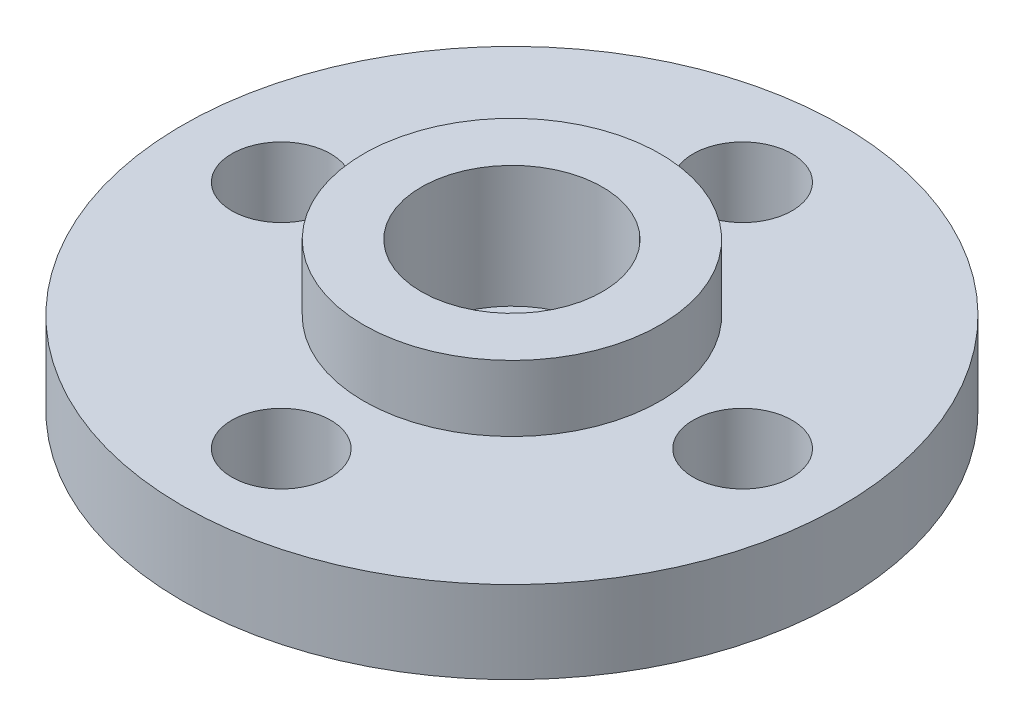
SolidWorks part; units mm, degrees
ref_plane "Front Plane" through (0, 0, 0) normal (0, 0, 1) x (1, 0, 0)
ref_plane "Top Plane" through (0, 0, 0) normal (0, 1, 0) x (1, 0, 0)
ref_plane "Right Plane" through (0, 0, 0) normal (1, 0, 0) x (0, 0, -1)
sketch "Sketch1" plane through (0, 0, 0) normal (0, 1, 0) x (1, 0, 0)
  circle A0 centre (0, 0) radius 10
  circle A1 centre (0, 0) radius 7 construction
  circle A2 centre (0, 7) radius 1.5
  circle A3 centre (7, 0) radius 1.5
  circle A4 centre (0, -7) radius 1.5
  circle A5 centre (-7, 0) radius 1.5
  circle A6 centre (0, 0) radius 1.5
  point P15 (0, 0)
  dimension "D1" = 20
  dimension "D2" = 14
  dimension "D3" = 3
  dimension "D4" = 4
extrude "Boss-Extrude1" add sketch "Sketch1" along normal blind 2.5
sketch "Sketch2" plane through (0, 2.5, 0) normal (0, 1, 0) x (1, 0, 0)
  circle A0 centre (0, 0) radius 4.5
  circle A1 centre (0, 0) radius 1.5 construction
  circle A2 centre (0, 0) radius 1.5
  dimension "D1" = 9
extrude "Boss-Extrude2" add sketch "Sketch2" along normal blind 2
sketch "Sketch3" plane through (0, 4.5, 0) normal (0, 1, 0) x (1, 0, 0)
  circle A0 centre (0, 0) radius 2.75
  dimension "D1" = 5.5
extrude "Cut-Extrude1" cut sketch "Sketch3" against normal blind 3.7
